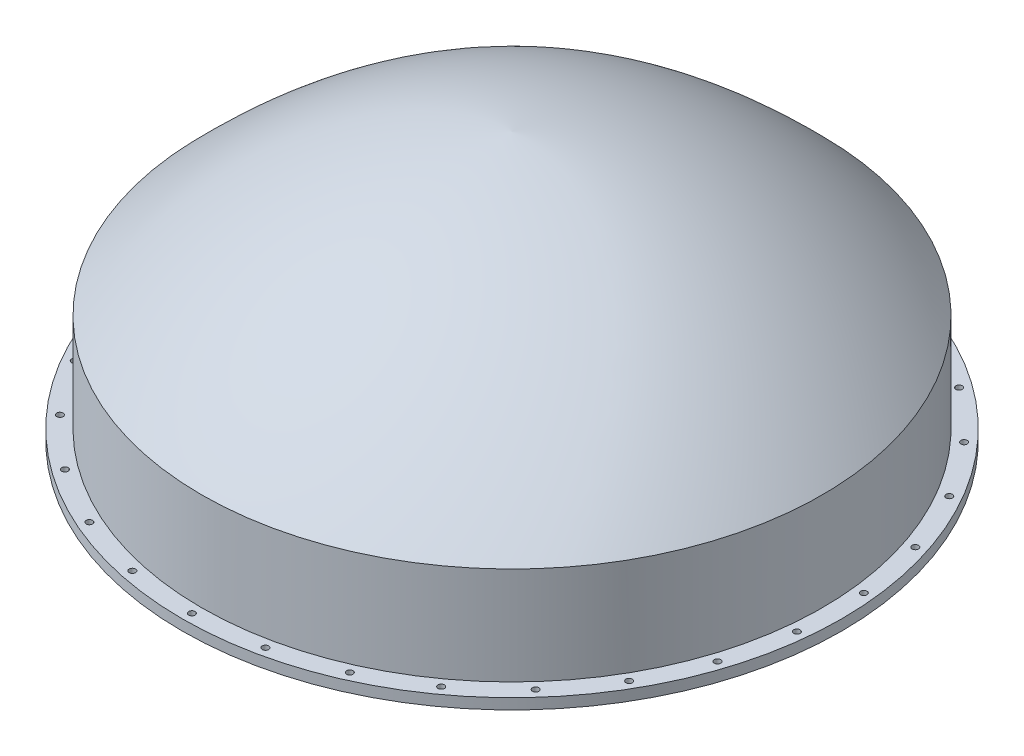
SolidWorks part; units mm, degrees
ref_plane "Front Plane" through (0, 0, 0) normal (0, 0, 1) x (1, 0, 0)
ref_plane "Top Plane" through (0, 0, 0) normal (0, 1, 0) x (1, 0, 0)
ref_plane "Right Plane" through (0, 0, 0) normal (1, 0, 0) x (0, 0, -1)
sketch "Sketch2" plane through (0, 0, 0) normal (1, 0, 0) x (0, 0, -1)
  line L0 (0, 0) -> (2427.7874, 0) construction
  line L1 (0, 0) -> (0, 2804.3081) construction
  line L2 (-2081.1295, -171.115) -> (-2081.1295, 0)
  line L3 (-2130.0195, -171.115) -> (-2130.0195, -671.115)
  line L4 (-2130.0195, -671.115) -> (-2262.0195, -671.115)
  line L5 (-2130.0195, -171.115) -> (-2130.0195, 0)
  line L7 (-2262.0195, -671.115) -> (-2262.0195, -744.115)
  line L8 (-2262.0195, -744.115) -> (-2081.1295, -744.115)
  line L9 (0, 1093.3) -> (0, 1044.41)
  line L10 (-2081.1295, -744.115) -> (-2081.1295, -171.115)
  spline S0 degree 2 poles (-2130.0195, 0) (-1162.829, 997.3651) (0, 1093.3) knots 0 0 0 0.824504 0.824504 0.824504
  spline S2 degree 2 poles (-2081.1295, 0) (-1041.8652, 973.9069) (0, 1044.41) knots 0 0 0 1 1 1
  dimension "D1" = 48.89
  dimension "D2" = 1093.3
  dimension "D3" = 500
  dimension "D4" = 48.89
  dimension "D5" = 132
  dimension "D6" = 73
  dimension "D7" = 2081.1295
revolve "Revolve3" add sketch "Sketch2" angle 360 about L9
ref_plane "Plane1" through (0, -744.115, 0) normal (0, -1, 0) x (1, 0, 0)
sketch "Sketch7" plane through (0, -744.115, 0) normal (0, -1, 0) x (1, 0, 0)
  line L0 (0, 0) -> (0, 2196.0195) construction
  circle A1 centre (0, 2196.0195) radius 22
  circle A2 centre (456.5781, 2148.0312) radius 22
  circle A3 centre (893.2016, 2006.1636) radius 22
  circle A4 centre (1290.7879, 1776.6171) radius 22
  circle A5 centre (1631.9605, 1469.4239) radius 22
  circle A6 centre (1901.8087, 1098.0097) radius 22
  circle A7 centre (2088.5387, 678.6073) radius 22
  circle A8 centre (2183.9895, 229.5465) radius 22
  circle A9 centre (2183.9895, -229.5465) radius 22
  circle A10 centre (2088.5387, -678.6073) radius 22
  circle A11 centre (1901.8087, -1098.0098) radius 22
  circle A12 centre (1631.9605, -1469.4239) radius 22
  circle A13 centre (1290.7879, -1776.6171) radius 22
  circle A14 centre (893.2016, -2006.1636) radius 22
  circle A15 centre (456.5781, -2148.0312) radius 22
  circle A16 centre (0, -2196.0195) radius 22
  circle A17 centre (-456.5781, -2148.0312) radius 22
  circle A18 centre (-893.2016, -2006.1636) radius 22
  circle A19 centre (-1290.7879, -1776.6171) radius 22
  circle A20 centre (-1631.9605, -1469.4239) radius 22
  circle A21 centre (-1901.8087, -1098.0097) radius 22
  circle A22 centre (-2088.5387, -678.6073) radius 22
  circle A23 centre (-2183.9895, -229.5465) radius 22
  circle A24 centre (-2183.9895, 229.5465) radius 22
  circle A25 centre (-2088.5387, 678.6073) radius 22
  circle A26 centre (-1901.8087, 1098.0098) radius 22
  circle A27 centre (-1631.9605, 1469.4239) radius 22
  circle A28 centre (-1290.7879, 1776.6171) radius 22
  circle A29 centre (-893.2016, 2006.1636) radius 22
  circle A30 centre (-456.5781, 2148.0312) radius 22
  dimension "D2" = 44
  dimension "D1" = 30
  dimension "D3" = 2196.0195
extrude "Cut-Extrude1" cut sketch "Sketch7" against normal blind 500
